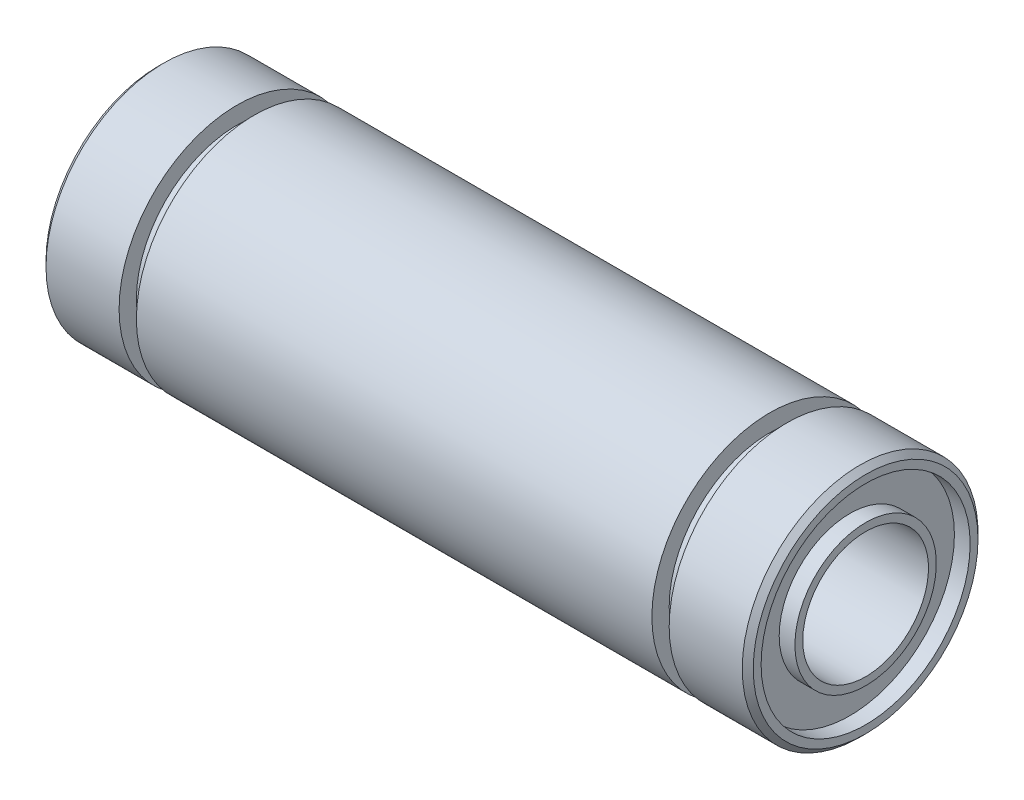
SolidWorks part; units mm, degrees
material "1060 Alloy"
ref_plane "Front Plane" through (0, 0, 0) normal (0, 0, 1) x (1, 0, 0)
ref_plane "Top Plane" through (0, 0, 0) normal (0, 1, 0) x (1, 0, 0)
ref_plane "Right Plane" through (0, 0, 0) normal (1, 0, 0) x (0, 0, -1)
sketch "Sketch1" plane through (0, 0, 0) normal (0, 0, 1) x (1, 0, 0)
  line L0 (-45.6895, 0) -> (45.6895, 0) construction
  line L1 (-22.15, 7.5) -> (-17.5, 7.5)
  line L2 (-17.5, 7.5) -> (-17.5, 6.4)
  line L3 (-17.5, 6.4) -> (-16.4, 6.4)
  line L4 (-16.4, 6.4) -> (-16.4, 7.5)
  line L5 (-16.4, 7.5) -> (16.4, 7.5)
  line L6 (0, 45.6895) -> (0, -45.6895) construction
  line L7 (-22.15, 7.5) -> (-22.5, 7.15)
  line L8 (-22.5, 7.15) -> (-22.5, 6.65)
  line L9 (-22.5, 6.65) -> (-21.5, 6.65)
  line L10 (-21.5, 6.65) -> (-21.5, 4.5)
  line L11 (-21.5, 4.5) -> (-22.5, 4.5)
  line L12 (-22.5, 4.5) -> (-22.5, 4)
  line L13 (-22.5, 4) -> (22.5, 4)
  line L14 (22.5, 4.5) -> (22.5, 4)
  line L15 (21.5, 4.5) -> (22.5, 4.5)
  line L16 (21.5, 6.65) -> (21.5, 4.5)
  line L17 (22.5, 6.65) -> (21.5, 6.65)
  line L18 (22.5, 7.15) -> (22.5, 6.65)
  line L19 (22.15, 7.5) -> (22.5, 7.15)
  line L20 (16.4, 6.4) -> (16.4, 7.5)
  line L21 (17.5, 6.4) -> (16.4, 6.4)
  line L22 (17.5, 7.5) -> (17.5, 6.4)
  line L23 (22.15, 7.5) -> (17.5, 7.5)
  point P19 (0, 4)
  point P26 (0, 7.5)
  dimension "D1" = 45
  dimension "D2" = 1.1
  dimension "L" = 45
  dimension "B" = 35
  dimension "W" = 1.1
  dimension "D" = 7.5
  dimension "D_1" = 7.15
  dimension "D3" = 0.5
  dimension "dr" = 4
  dimension "D4" = 0.5
  dimension "D5" = 1
revolve "Revolve1" add sketch "Sketch1" angle 360 about L0
equation "\"D\"=15"
equation "\"D1\"=14.3"
equation "\"dr\"=8"
equation "\"L\"=45"
equation "\"B\"=35"
equation "\"W\"=1.1"
equation "\"L@Sketch1\"= \"L\""
equation "\"B@Sketch1\"= \"B\""
equation "\"W@Sketch1\"= \"W\""
equation "\"dr@Sketch1\"= \"dr\" * 0.5"
equation "\"D@Sketch1\" = \"D\" * 0.5"
equation "\"D_1@Sketch1\" = \"D1\" * 0.5"
